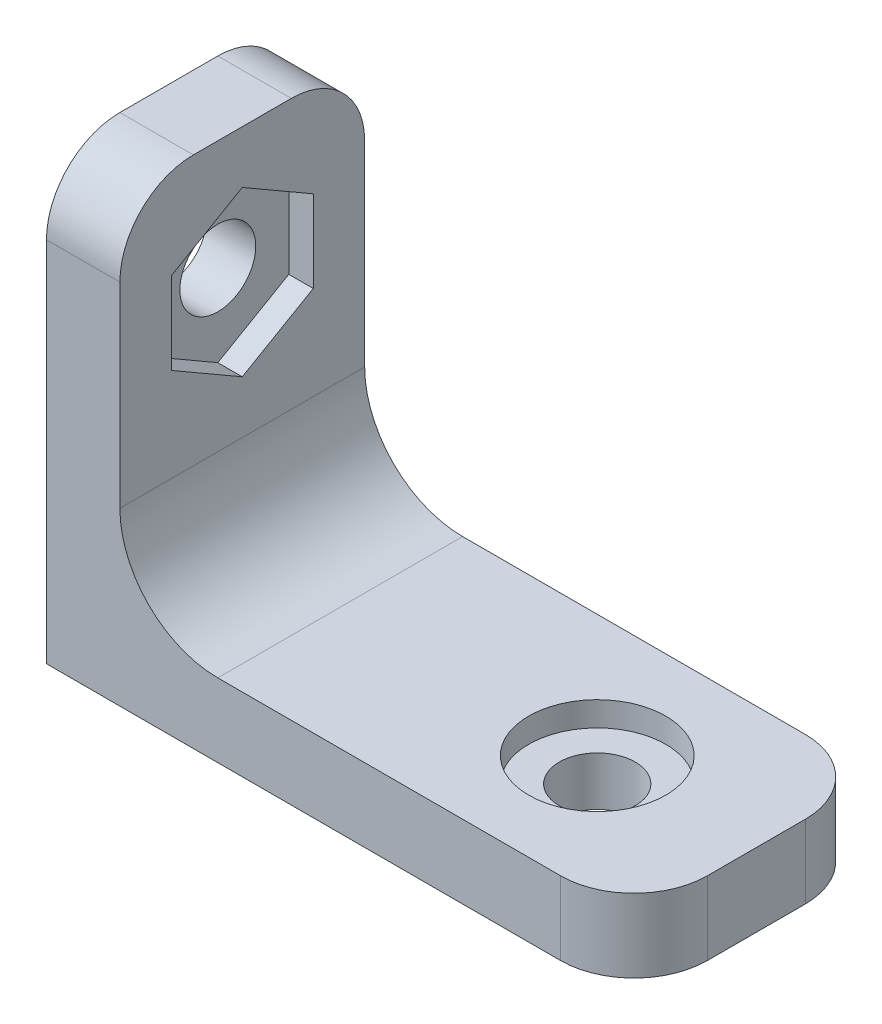
SolidWorks part; units mm, degrees
ref_plane "Alzado" through (0, 0, 0) normal (0, 0, 1) x (1, 0, 0)
ref_plane "Planta" through (0, 0, 0) normal (0, 1, 0) x (1, 0, 0)
ref_plane "Vista lateral" through (0, 0, 0) normal (1, 0, 0) x (0, 0, -1)
sketch "Croquis1" plane through (0, 0, 0) normal (0, 1, 0) x (1, 0, 0)
  line L1 (0, 0) -> (24, 0)
  line L2 (0, 0) -> (0, 10)
  line L3 (0, 10) -> (24, 10)
  line L4 (24, 0) -> (24, 10)
  circle A0 centre (17.5, 5) radius 1.55
  dimension "D3" = 3.1
  dimension "D1" = 24
  dimension "D2" = 10
  dimension "D4" = 17.5
  dimension "D5" = 5
extrude "Saliente-Extruir1" add sketch "Croquis1" along normal blind 3
sketch "Croquis2" plane through (0, 3, 0) normal (0, 1, 0) x (1, 0, 0)
  line L0 (0, 0) -> (24, 0) construction
  line L1 (0, 10) -> (3, 10)
  line L2 (0, 10) -> (0, 0)
  line L3 (0, 0) -> (3, 0)
  line L4 (3, 10) -> (3, 0)
  dimension "D1" = 3
extrude "Saliente-Extruir2" add sketch "Croquis2" along normal blind 15
sketch "Croquis3" plane through (0, 0, 0) normal (-1, 0, 0) x (0, 0, 1)
  line L0 (-10, 0) -> (0, 0) construction
  line L1 (0, 18) -> (0, 0) construction
  circle A0 centre (-5, 12.5) radius 1.55
  dimension "D1" = 3.1
  dimension "D2" = 12.5
  dimension "D3" = 5
extrude "Cortar-Extruir1" cut sketch "Croquis3" against normal up to surface (3 mm away) up to face at (3, 10.5, -5)
sketch "Croquis4" plane through (0, 3, 0) normal (0, 1, 0) x (1, 0, 0)
  circle A0 centre (17.5, 5) radius 2.8
  dimension "D1" = 5.6
extrude "Cortar-Extruir2" cut sketch "Croquis4" against normal blind 1
sketch "Croquis5" plane through (3, 0, 0) normal (1, 0, 0) x (0, 0, -1)
  line L1 (7.9, 14.1743) -> (5, 15.8486)
  line L2 (5, 15.8486) -> (2.1, 14.1743)
  line L3 (2.1, 14.1743) -> (2.1, 10.8257)
  line L4 (2.1, 10.8257) -> (5, 9.1514)
  line L5 (5, 9.1514) -> (7.9, 10.8257)
  line L6 (7.9, 10.8257) -> (7.9, 14.1743)
  line L8 (10, 18) -> (10, 3) construction
  circle A0 centre (5, 12.5) radius 2.9 construction
  dimension "D1" = 5.8
extrude "Cortar-Extruir3" cut sketch "Croquis5" against normal blind 1
fillet "Redondeo1" radius 3 4 edges at (1.5, 18, -10) (1.5, 18, 0) (24, 1.5, 0) (24, 1.5, -10)
fillet "Redondeo2" radius 4 1 edges at (3, 3, -5)
